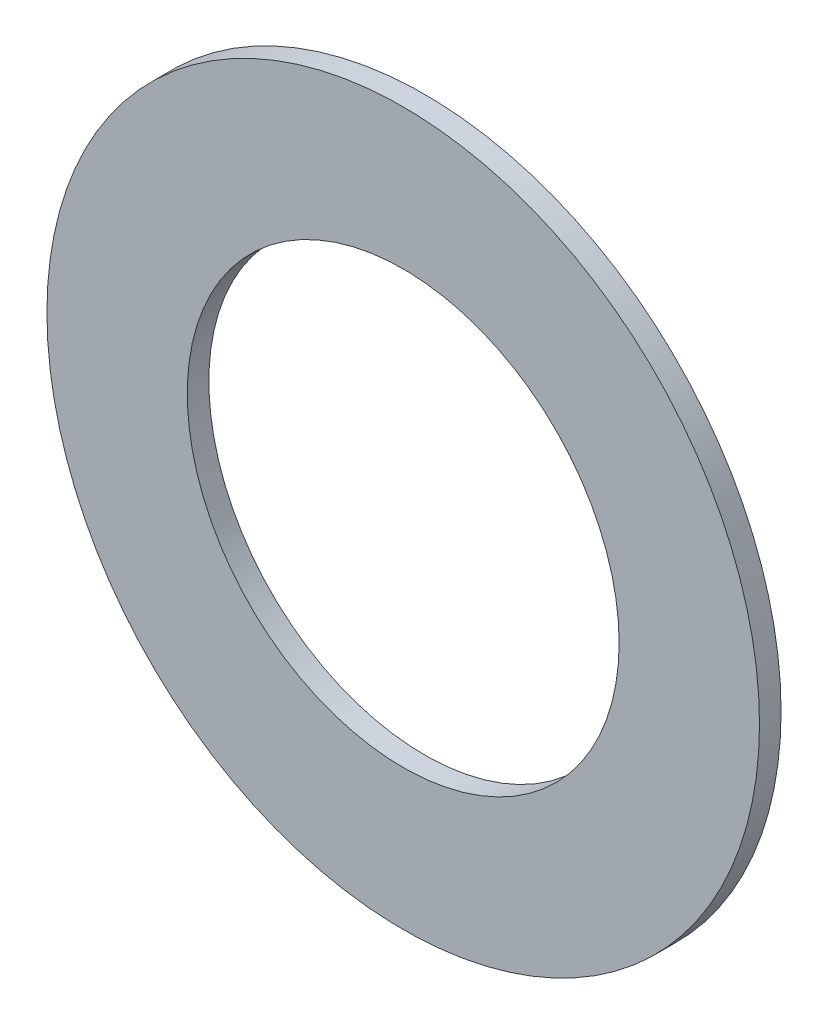
SolidWorks part; units mm, degrees
ref_plane "Front Plane" through (0, 0, 0) normal (0, 0, 1) x (1, 0, 0)
ref_plane "Top Plane" through (0, 0, 0) normal (0, 1, 0) x (1, 0, 0)
ref_plane "Right Plane" through (0, 0, 0) normal (1, 0, 0) x (0, 0, -1)
sketch "Sketch1" plane through (0, 0, 0) normal (0, 0, 1) x (1, 0, 0)
  circle A0 centre (0, 0) radius 16.5
extrude "Boss-Extrude1" add sketch "Sketch1" along normal blind 1
sketch "Sketch2" plane through (0, 0, 0) normal (0, 0, 1) x (1, 0, 0)
  circle A0 centre (0, 0) radius 10
extrude "Cut-Extrude1" cut sketch "Sketch2" against normal through all and the other way through all
